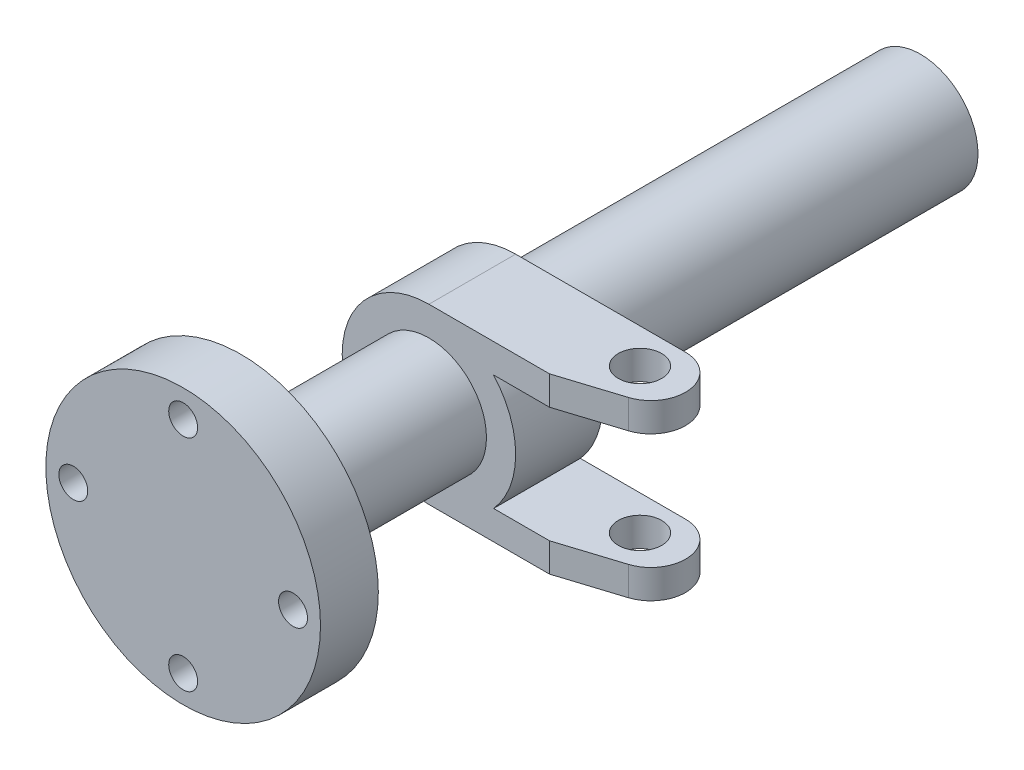
SolidWorks part; units mm, degrees
ref_plane "Front Plane" through (0, 0, 0) normal (0, 0, 1) x (1, 0, 0)
ref_plane "Top Plane" through (0, 0, 0) normal (0, 1, 0) x (1, 0, 0)
ref_plane "Right Plane" through (0, 0, 0) normal (1, 0, 0) x (0, 0, -1)
sketch "Sketch1" plane through (0, 0, 0) normal (0, 1, 0) x (1, 0, 0)
  line L0 (0, 0) -> (0, 255) construction
  line L1 (0, 255) -> (19.9, 255)
  line L2 (19.9, 255) -> (19.9, 115)
  line L3 (19.9, 115) -> (30, 115)
  line L4 (30, 115) -> (30, 85)
  line L5 (30, 85) -> (19.9, 85)
  line L6 (19.9, 85) -> (19.9, 20)
  line L7 (19.9, 20) -> (47.5, 20)
  line L8 (47.5, 20) -> (47.5, 0)
  line L9 (47.5, 0) -> (0, 0)
  line L10 (0, 0) -> (0, 255)
  point P3 (47.5, 10)
  dimension "D1" = 255
  dimension "D2" = 19.9
  dimension "D3" = 30
  dimension "D4" = 19.9
  dimension "D5" = 47.5
  dimension "D6" = 140
  dimension "D7" = 30
  dimension "D8" = 65
revolve "Revolve1" add sketch "Sketch1" angle 360 about L0
ref_plane "Plane1" through (0, 30, 0) normal (0, 1, 0) x (1, 0, 0)
sketch "Sketch2" plane through (0, 30, 0) normal (0, 1, 0) x (1, 0, 0)
  line L0 (0, 115) -> (0, 214.1423) construction
  line L2 (30, 115) -> (-30, 115) construction
  line L7 (0, 115) -> (58.75, 115)
  line L10 (0, 115) -> (0, 85)
  line L11 (-19.9, 85) -> (19.9, 85) construction
  line L12 (0, 85) -> (30, 85)
  line L19 (41.6842, 85) -> (30, 85)
  line L20 (60, 90.8076) -> (41.6842, 85)
  line L21 (55, 103) -> (62.5, 103) construction
  line L22 (60, 115) -> (60, 85) construction
  line L23 (60, 90.8076) -> (62.377, 91.5613)
  circle A2 centre (55, 103) radius 7.5
  arc A3 (62.377, 91.5613) -> (58.75, 115) centre (58.75, 103) ccw
  dimension "D1" = 55
  dimension "D4" = 24
  dimension "15" = 15
  dimension "D2" = 12
  dimension "D3" = 60
extrude "Boss-Extrude1" add sketch "Sketch2" against normal blind 10
mirror "Mirror1" about plane through (0, 0, 0) normal (0, 1, 0) of "Boss-Extrude1"
hole_wizard "CBORE for M5 Hex Head Bolt1" positions "Sketch3" profile "Sketch4" counterbore size "M5" standard "ISO" end condition through all
sketch "Sketch3" plane through (0, 0, -20) normal (0, 0, -1) x (-1, 0, 0)
  circle A0 centre (0, 0) radius 38 construction
  point P0 (0, 38)
  dimension "D1" = 76
sketch "Sketch4" plane through (0, 38, -20) normal (1, 0, 0) x (0, 1, 0)
  line L0 (0, 0) -> (0, 20)
  line L1 (0, 20) -> (5, 20)
  line L3 (5, 20) -> (5, 10)
  line L4 (5, 10) -> (7, 10)
  line L5 (7, 10) -> (7, 0)
  line L7 (7, 0) -> (0, 0)
  line L11 (0, -6.35) -> (0, 107.95) construction
  dimension "Thru Hole Dia." = 10
  dimension "Thru Hole Depth" = 20
  dimension "C'Bore Dia." = 14
  dimension "C'Bore Depth" = 10
pattern_circular "CirPattern1" count 4 over 360 about axis through (0, 0, 0) along (0, 0, 1) of "CBORE for M5 Hex Head Bolt1"
